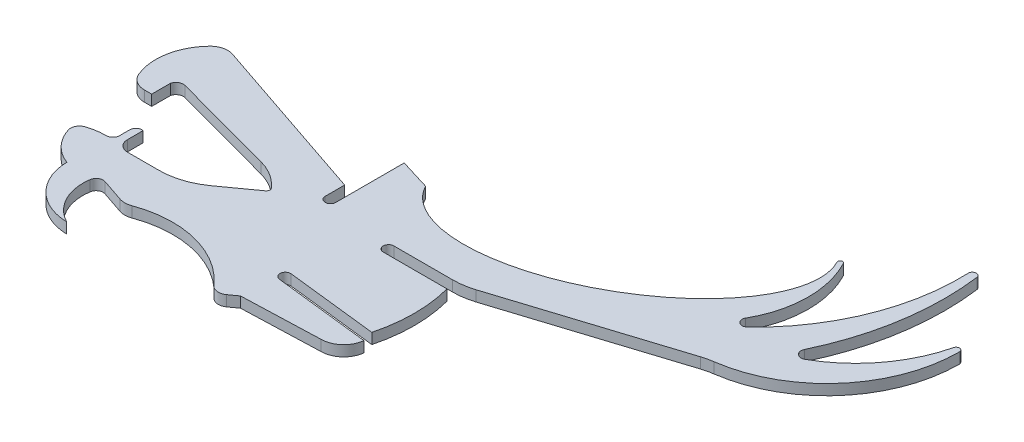
SolidWorks part; units mm, degrees
ref_plane "Front Plane" through (0, 0, 0) normal (0, 0, 1) x (1, 0, 0)
ref_plane "Top Plane" through (0, 0, 0) normal (0, 1, 0) x (1, 0, 0)
ref_plane "Right Plane" through (0, 0, 0) normal (1, 0, 0) x (0, 0, -1)
sketch "Sketch1" plane through (0, 0, 0) normal (0, 1, 0) x (1, 0, 0)
  line L0 (3.2405, 9.6617) -> (79.7861, 49.126) construction
  line L1 (83.6397, 6.7645) -> (35.6672, -8.4963)
  line L2 (29.9074, -9.3903) -> (13.3316, -9.3903)
  line L3 (13.3316, -12.3903) -> (31.3356, -12.3903)
  line L4 (31.3356, -12.3903) -> (31.3356, -33.6115) construction
  line L5 (31.3356, -33.6115) -> (5.6729, -30.6876)
  line L6 (5.3333, -33.6683) -> (32.2588, -36.7361)
  line L7 (3.9316, -43.2347) -> (25.8383, -42.4665)
  line L8 (3.9316, -43.2347) -> (1.645, -44.8795)
  line L9 (-36.732, -36.5554) -> (-43.072, -34.4135)
  line L10 (-52.2665, -21.1248) -> (-52.2665, -18.2553)
  line L11 (-50.5665, -16.5553) -> (-50.185, -16.5553)
  line L12 (-50.185, -16.5553) -> (-50.185, -21.009)
  line L13 (-47.1388, -24.0553) -> (-38.2581, -24.0553)
  line L14 (-27.1635, -20.4796) -> (-18.2139, -14.0423)
  line L15 (-25.9633, -7.5659) -> (-55.3095, 0.3493)
  line L16 (-57.8833, -1.131) -> (-57.8833, -6.4672)
  line L17 (-57.8833, -6.4672) -> (-59.9704, -6.4672)
  line L18 (-56.2151, 14.68) -> (-8.4656, -1.452)
  line L19 (-8.4656, -1.452) -> (-8.4656, -6.952)
  line L20 (-5.4656, -6.952) -> (-5.4656, 12.3362)
  line L21 (-5.4656, 12.3362) -> (3.2405, 9.6617)
  arc A0 (79.7861, 49.126) -> (80.9805, 49.7504) centre (80.3851, 49.4348) cw
  arc A1 (80.9805, 49.7504) -> (80.573, 22.6111) centre (56.0778, 36.5516) cw
  arc A2 (80.573, 22.6111) -> (83.0608, 20.6663) centre (81.96, 21.8217) ccw
  arc A3 (83.0608, 20.6663) -> (100.9952, 64.9318) centre (43.0842, 62.6289) ccw
  arc A4 (100.9952, 64.9318) -> (103.2344, 65.122) centre (102.1191, 64.9765) cw
  arc A5 (103.2344, 65.122) -> (96.5249, 23.2259) centre (29.2943, 55.4779) cw
  arc A6 (96.5249, 23.2259) -> (99.0346, 20.8776) centre (98.1492, 22.4466) ccw
  arc A7 (99.0346, 20.8776) -> (117.0982, 44.703) centre (80.5346, 53.664) ccw
  arc A8 (117.0982, 44.703) -> (118.9683, 44.4772) centre (118.0196, 44.4772) cw
  arc A10 (118.9683, 44.4772) -> (86.773, 7.4761) centre (81.6086, 44.4772) cw
  arc A11 (13.3316, -9.3903) -> (13.3316, -12.3903) centre (13.3316, -10.8903) ccw
  arc A12 (5.6729, -30.6876) -> (5.3333, -33.6683) centre (5.5031, -32.178) ccw
  arc A13 (32.2588, -36.7361) -> (25.8383, -42.4665) centre (25.8383, -36.0046) cw
  arc A14 (-2.3631, -44.4212) -> (-33.4065, -36.5114) centre (-23.644, -63.0694) ccw
  arc A15 (-45.691, -36.0178) -> (-38.702, -49.6317) centre (-32.6625, -37.9303) ccw
  arc A16 (-38.702, -49.6317) -> (-53.199, -35.0885) centre (-38.4397, -34.8731) cw
  arc A17 (-53.199, -35.0885) -> (-60.8804, -27.0039) centre (-48.6613, -23.0856) cw
  arc A18 (-60.8804, -27.0039) -> (-59.2327, -23.8007) centre (-58.455, -26.2262) cw
  arc A19 (-59.2327, -23.8007) -> (-54.147, -23.0053) centre (-54.147, -39.6606) cw
  arc A20 (-54.147, -23.0053) -> (-52.2665, -21.1248) centre (-54.147, -21.1248) ccw
  arc A21 (-50.185, -21.009) -> (-47.1388, -24.0553) centre (-47.1388, -21.009) ccw
  arc A22 (-18.2139, -14.0423) -> (-18.0368, -12.5767) centre (-18.7996, -13.228) ccw
  arc A23 (-18.0368, -12.5767) -> (-25.9633, -7.5659) centre (-30.0913, -22.8707) ccw
  arc A24 (-55.3095, 0.3493) -> (-57.8833, -1.131) centre (-55.8563, -1.6778) ccw
  arc A25 (-64.5871, -3.3871) -> (-61.414, 13.4145) centre (-50.1997, 2.5961) cw
  arc A26 (-8.4656, -6.952) -> (-5.4656, -6.952) centre (-6.9656, -6.952) ccw
  arc A27 (-61.414, 13.4145) -> (-56.2151, 14.68) centre (-57.8155, 9.9431) cw
  arc A28 (-33.4065, -36.5114) -> (-36.732, -36.5554) centre (-35.1317, -31.8184) cw
  arc A29 (1.645, -44.8795) -> (-2.3631, -44.4212) centre (-0.1068, -42.444) cw
  arc A30 (-43.072, -34.4135) -> (-45.691, -36.0178) centre (-43.7122, -36.3083) ccw
  arc A31 (-52.2665, -18.2553) -> (-50.5665, -16.5553) centre (-50.5665, -18.2553) cw
  arc A32 (-59.9704, -6.4672) -> (-64.5871, -3.3871) centre (-59.9704, -1.4672) cw
  arc A33 (31.3356, -12.3903) -> (31.3356, -33.6115) centre (-9.027, -23.0009) cw
  arc A34 (-38.2581, -24.0553) -> (-27.1635, -20.4796) centre (-38.2581, -5.0553) ccw
  arc A35 (35.6672, -8.4963) -> (29.9074, -9.3903) centre (29.9074, 9.6097) cw
  arc A36 (86.773, 7.4761) -> (83.6397, 6.7645) centre (89.3995, -11.3415) ccw
  ellipse E0 centre (41.5133, 29.3938) end of major axis (3.2405, 9.6617) minor radius 23.25 (3.2405, 9.6617) -> (79.7861, 49.126) ccw
  point P82 (-32.1346, -24.0553)
  point P85 (32.8567, -9.3903)
  point P88 (85.3349, 7.3038)
  point P89 (-8.4656, -1.6778)
  point P90 (-8.4656, -1.6778)
  point P91 (0, 0)
  point P92 (-8.4656, -1.6778)
  point P93 (-57.8833, 9.6617)
  point P94 (0, 0)
  point P96 (-6.9656, -8.452)
  point P106 (-58.8363, 15.5656)
  point P109 (-34.9843, -37.1459)
  point P112 (-0.6734, -46.5471)
  point P115 (-45.1378, -33.7155)
  point P120 (-62.8746, -6.4672)
  dimension "D6" = 1.5
  dimension "D9" = 0.6739
  dimension "D10" = 28.1843
  dimension "D11" = 1.5959
  dimension "D12" = 57.9568
  dimension "D13" = 1.1247
  dimension "D14" = 74.5664
  dimension "D15" = 1.8016
  dimension "D16" = 37.6456
  dimension "D17" = 0.9487
  dimension "D18" = 37.3597
  dimension "D19" = 6.462
  dimension "D20" = 28.2955
  dimension "D21" = 13.168
  dimension "D22" = 14.7609
  dimension "D23" = 12.832
  dimension "D24" = 2.5471
  dimension "D25" = 16.6553
  dimension "D26" = 1.8805
  dimension "D27" = 3.0463
  dimension "D28" = 1.003
  dimension "D29" = 15.8517
  dimension "D30" = 2.0995
  dimension "D31" = 15.5819
  dimension "D60" = 5
  dimension "D61" = 5
  dimension "D62" = 3
  dimension "D63" = 2
  dimension "D64" = 1.7
  dimension "D65" = 5
  dimension "D68" = 19
  dimension "D69" = 19
  dimension "D70" = 19
  dimension "D1" = 46.5
  dimension "D2" = 6.5
  dimension "86.12" = 86.12
  dimension "D3" = 20.7882
  dimension "D4" = 7
  dimension "D5" = 102.71
  dimension "D7" = 6.45
  dimension "D8" = 7.5
  dimension "D32" = 3.2405
  dimension "D33" = 3.9316
  dimension "D34" = 5.3333
  dimension "D35" = 25.8383
  dimension "D36" = 29.2943
  dimension "D37" = 13.3316
  dimension "D38" = 30.859
  dimension "D39" = 43.0842
  dimension "D40" = 56.0778
  dimension "D41" = 31.3356
  dimension "D42" = 80.5346
  dimension "D43" = 32.8567
  dimension "D44" = 80.573
  dimension "D45" = 81.6086
  dimension "D46" = 96.5249
  dimension "D47" = 100.9952
  dimension "D48" = 0.6734
  dimension "D49" = 18.0368
  dimension "D50" = 18.2139
  dimension "D51" = 18.7996
  dimension "D52" = 25.9633
  dimension "D53" = 48.6613
  dimension "D54" = 52.2665
  dimension "D55" = 55.3095
  dimension "D56" = 85.3349
  dimension "D57" = 58.455
  dimension "D58" = 0.3493
  dimension "D59" = 2.5961
  dimension "D66" = 9.027
  dimension "D67" = 6.9656
  dimension "D74" = 32.1346
  dimension "D75" = 32.6625
  dimension "D76" = 34.9843
  dimension "D77" = 38.4397
  dimension "D78" = 38.702
  dimension "D79" = 45.1378
  dimension "D81" = 50.185
  dimension "D82" = 50.1997
  dimension "D84" = 53.199
  dimension "D87" = 57.8833
  dimension "D89" = 58.8363
  dimension "D92" = 62.8746
  dimension "D102" = 10.8903
extrude "Boss-Extrude2" add sketch "Sketch1" along normal blind 3
